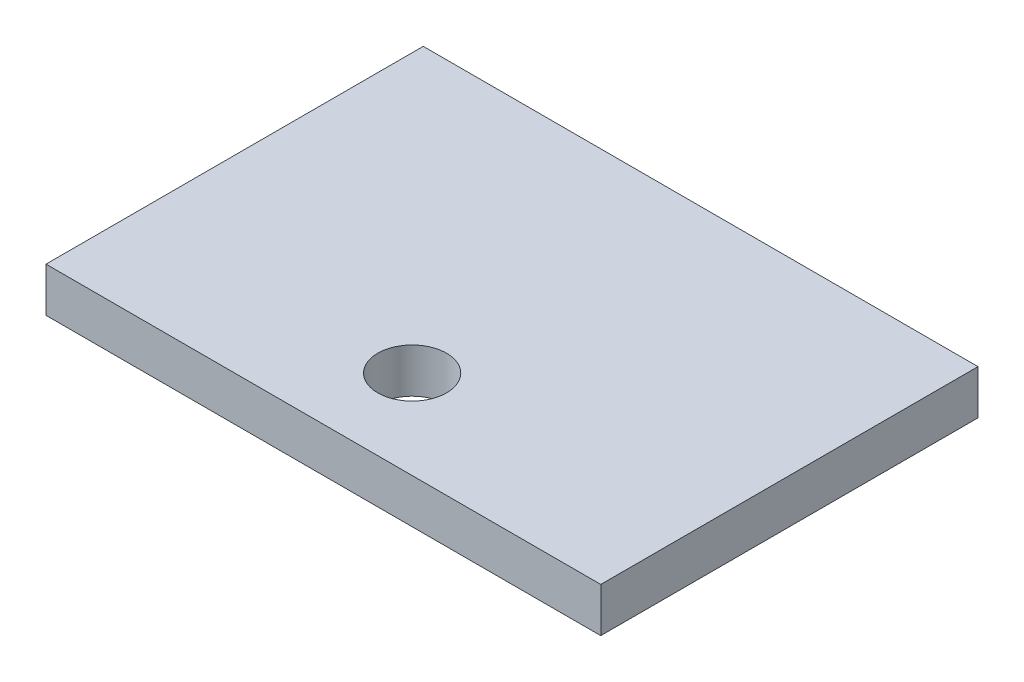
SolidWorks part; units mm, degrees
ref_plane "前视基准面" through (0, 0, 0) normal (0, 0, 1) x (1, 0, 0)
ref_plane "上视基准面" through (0, 0, 0) normal (0, 1, 0) x (1, 0, 0)
ref_plane "右视基准面" through (0, 0, 0) normal (1, 0, 0) x (0, 0, -1)
other "Configuration Table"
sketch "草图1" plane through (0, 0, 0) normal (0, 1, 0) x (1, 0, 0)
  line L1 (-12.5, -8.5) -> (12.5, -8.5)
  line L2 (-12.5, -8.5) -> (-12.5, 8.5)
  line L3 (-12.5, 8.5) -> (12.5, 8.5)
  line L4 (12.5, -8.5) -> (12.5, 8.5)
  line L5 (-12.5, -8.5) -> (12.5, 8.5) construction
  line L6 (-12.5, 8.5) -> (12.5, -8.5) construction
  circle A0 centre (0, -4.5) radius 1.55
  point P0 (0, 0)
  dimension "D4" = 3.1
  dimension "D1" = 25
  dimension "D2" = 17
  dimension "D3" = 13
extrude "凸台-拉伸1" add sketch "草图1" along normal blind 2
